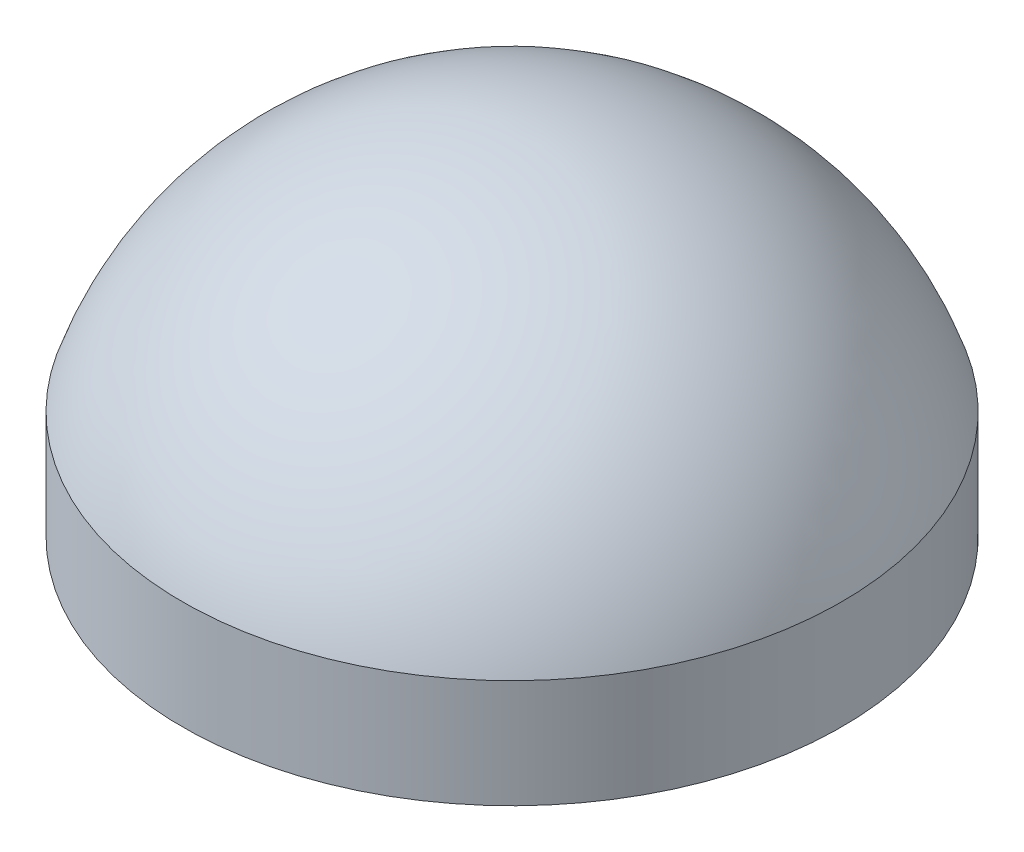
SolidWorks part; units mm, degrees
ref_plane "Front Plane" through (0, 0, 0) normal (0, 0, 1) x (1, 0, 0)
ref_plane "Top Plane" through (0, 0, 0) normal (0, 1, 0) x (1, 0, 0)
ref_plane "Right Plane" through (0, 0, 0) normal (1, 0, 0) x (0, 0, -1)
sketch "Sketch1" plane through (0, 0, 0) normal (0, 1, 0) x (1, 0, 0)
  line L0 (-13, 0) -> (-20, 0)
  line L1 (13, 0) -> (20, 0)
  arc A0 (20, 0) -> (-20, 0) centre (0, 0) ccw
  arc A1 (13, 0) -> (-13, 0) centre (0, 0) ccw
  dimension "D1" = 40
  dimension "D2" = 26
revolve "Revolve1" add sketch "Sketch1" angle 180 about L1
sketch "Sketch2" plane through (0, 0, 0) normal (1, 0, 0) x (0, 0, -1)
  line L0 (0, 0) -> (0, 15.1959) construction
  line L1 (-21.135, 0) -> (-19, 0)
  line L2 (-21.135, 0) -> (-21.135, 6.25)
  line L3 (-21.135, 6.25) -> (-19, 6.25)
  line L4 (-19, 0) -> (-19, 6.25)
  dimension "D1" = 19
  dimension "D2" = 21.135
  dimension "D3" = 6.25
revolve "Cut-Revolve1" cut sketch "Sketch2" angle 360 about L0
